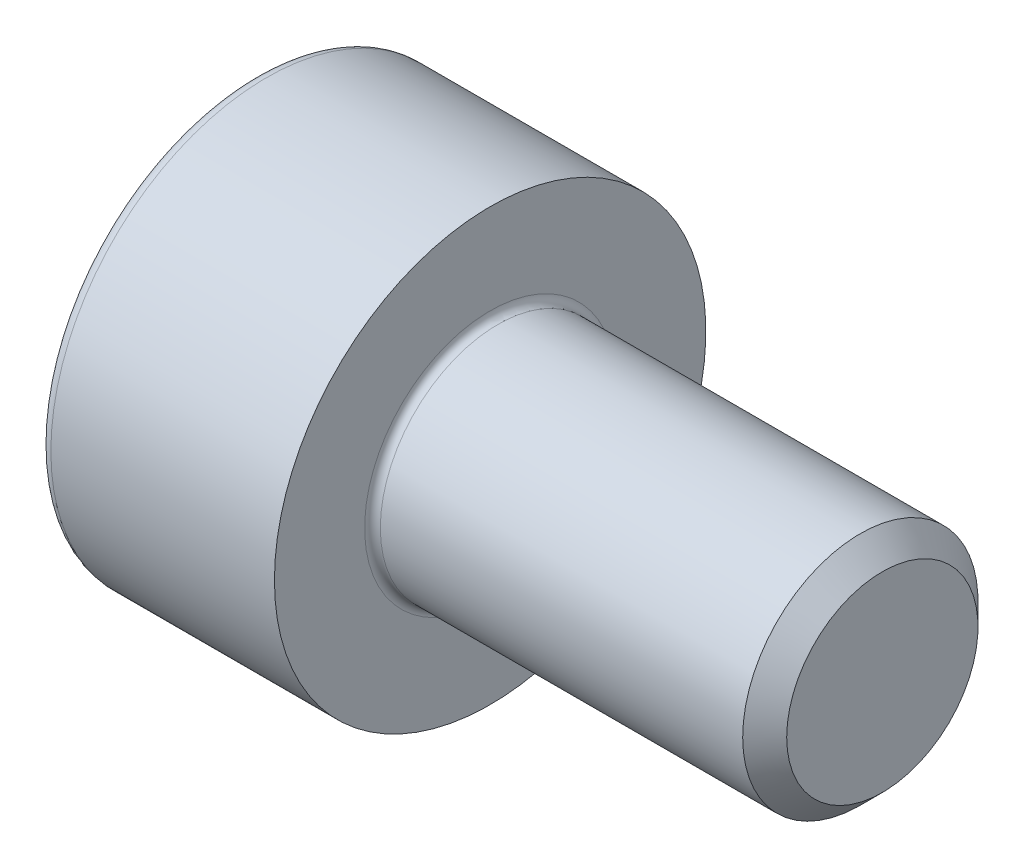
SolidWorks part; units mm, degrees
revolve "Base-Revolve" add sketch "BodySke"
sketch "BodySke" plane through (0, 0, 0) normal (0, 0, 1) x (1, 0, 0)
  line L0 (0, 0) -> (0, 2.75)
  line L1 (0, 2.75) -> (3, 2.75)
  line L2 (3, 2.75) -> (3, 1.5)
  line L3 (3, 1.5) -> (7.7195, 1.5)
  line L4 (8, 1.2195) -> (8, 0)
  line L5 (8, 0) -> (0, 0)
  line L6 (-31.75, 0) -> (127, 0) construction
  line L8 (8, 1.2195) -> (7.7195, 1.5)
  line L10 (8, -1.2195) -> (7.7195, -1.5) construction
  line L11 (3.5, 9.525) -> (3.5, 3.175) construction
  line L12 (3, 9.525) -> (3, 3.175) construction
  line L13 (-52, 9.525) -> (-52, 3.175) construction
  dimension "Head_ht" = 3
  dimension "Length" = 5
  dimension "Body_ch_ang" = 45
  dimension "Diameter" = 3
  dimension "Minor_dia" = 2.439
  dimension "Advance" = 0.5
  dimension "Thread_nom" = 5
  dimension "Thread_length" = 60
  dimension "Head_dia" = 5.5
cosmetic thread "ThreadCosmetic" [suppressed]
fillet "Fillet1" radius 0.1 1 edges at (3, 0, 1.5)
fillet "Fillet2" radius 0.15 1 edges at (0, 0, 2.75)
ref_plane "Plane1" through (0, 0, 0) normal (0, 0, 1) x (1, 0, 0)
ref_plane "Plane2" through (0, 0, 0) normal (0, 1, 0) x (1, 0, 0)
ref_plane "Plane3" through (0, 0, 0) normal (1, 0, 0) x (0, 0, -1)
other "Configuration Table"
sketch "Sketch2" plane through (0, 0, 0) normal (0, 0, 1) x (1, 0, 0)
  line L0 (0, 1.28) -> (1.3, 1.28)
  line L1 (1.3, 1.28) -> (2.039, 0)
  line L2 (-31.75, 0) -> (127, 0) construction
  line L3 (2.039, 0) -> (0, 0)
  line L4 (0, 0) -> (0, 1.28)
  line L6 (0, 0) -> (47.625, 0) construction
  dimension "D1" = 1.28
  dimension "D2" = 60
  dimension "Depth" = 1.3
revolve "Hex-PreBroach" cut sketch "Sketch2" angle 360 about L6
sketch "Sketch3" plane through (0, 0, 0) normal (-1, 0, 0) x (0, 0.5, 0.866)
  line L0 (0.739, 1.28) -> (-0.739, 1.28)
  line L1 (-0.739, 1.28) -> (-1.478, 0)
  line L2 (0.739, 1.28) -> (1.478, 0)
  line L3 (0.739, -1.28) -> (1.478, 0)
  line L4 (0.739, -1.28) -> (-0.739, -1.28)
  line L5 (-0.739, -1.28) -> (-1.478, 0)
  dimension "D1" = 1.28
  dimension "D2" = 1.28
  dimension "Hex_size" = 2.56
extrude "Hex" cut sketch "Sketch3" against normal blind 1.3
sketch "ThdSchSke" plane through (0, 0, 0) normal (0, 0, 1) x (1, 0, 0)
  line L0 (4.5, -1.2195) -> (4.3036, -1.5)
  line L1 (4.5, -1.2195) -> (4.6964, -1.5)
  line L2 (4.6964, -1.5) -> (4.6964, -1.875)
  line L3 (-3.175, 0) -> (5.1513, 0) construction
  line L4 (0, 2.6) -> (0, -2.6) construction
  line L5 (4.6964, -1.875) -> (4.3036, -1.875)
  line L6 (4.3036, -1.875) -> (4.3036, -1.5)
  dimension "Thread_minor" = 2.439
  dimension "Diameter" = 3
  dimension "Start" = 4.5
revolve "ThreadSchematic" [suppressed] cut sketch "ThdSchSke" angle 360 about L3
pattern_linear "ThdSchPat" [suppressed]
equation "\"D2@Sketch3\" = \"Hex_size@Sketch3\" / 2"
equation "\"D1@Sketch3\" = \"Hex_size@Sketch3\" / 2"
equation "\"D1@Sketch2\" = \"Hex_size@Sketch3\" / 2"
equation "\"Thread_minor@ThreadCosmetic\"  =  \"Minor_dia@BodySke\""
equation "\"Depth@Sketch2\" =  \"Key_eng@Hex\""
equation "\"Thread_length@ThreadCosmetic\" = ((sgn( (\"Length@BodySke\" - \"Advance@BodySke\" * 3.0) - \"Thread_nom@BodySke\" )-1)*( (\"Length@BodySke\" - \"Advance@BodySke\" * 3.0) - \"Thread_nom@BodySke\" ))/-2+ \"Thread_nom@BodySke\""
equation "\"Thread_minor@ThdSchSke\" = \"Minor_dia@BodySke\""
equation "\"Diameter@ThdSchSke\" = \"Diameter@BodySke\""
equation "\"Overcut@ThdSchSke\" = \"Diameter@BodySke\" * 1.25"
equation "\"Start@ThdSchSke\" = \"Head_ht@BodySke\" + \"Length@BodySke\" - \"Thread_length@ThreadCosmetic\"  '---Non-countersunk---"
equation "\"Num_threads@ThdSchPat\" = int( \"Thread_length@ThreadCosmetic\" / \"Advance@BodySke\" + 0.999 )  + 1"
equation "\"Advance@ThdSchPat\" = \"Thread_length@ThreadCosmetic\" /  (\"Num_threads@ThdSchPat\" - 1) 'relax it"
equation "\"Num_threads@ThdSchPat\" = \"Num_threads@ThdSchPat\" - sgn( \"Num_threads@ThdSchPat\" - 1) '---chamfered tips only---"
